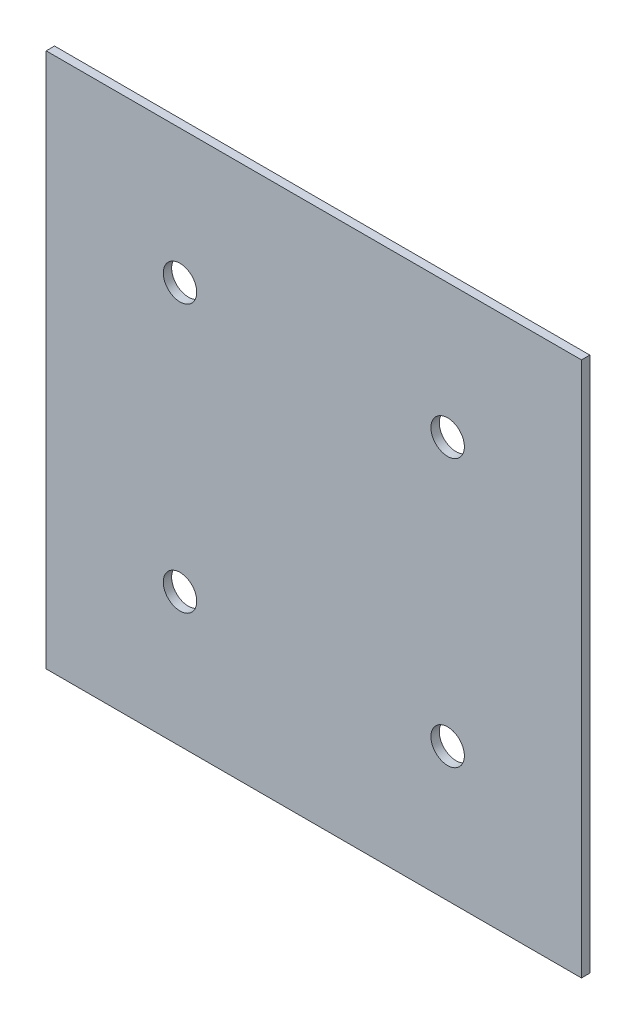
SolidWorks part; units mm, degrees
ref_plane "前视基准面" through (0, 0, 0) normal (0, 0, 1) x (1, 0, 0)
ref_plane "上视基准面" through (0, 0, 0) normal (0, 1, 0) x (1, 0, 0)
ref_plane "右视基准面" through (0, 0, 0) normal (1, 0, 0) x (0, 0, -1)
sketch "草图1" plane through (0, 0, 0) normal (0, 0, 1) x (1, 0, 0)
  line L1 (0, 0) -> (160, 0)
  line L2 (0, 0) -> (0, 160)
  line L3 (0, 160) -> (160, 160)
  line L4 (160, 0) -> (160, 160)
  dimension "D1" = 160
  dimension "D2" = 160
extrude "凸台-拉伸1" add sketch "草图1" along normal blind 2.5
sketch "草图2" plane through (0, 0, 2.5) normal (0, 0, 1) x (1, 0, 0)
  line L0 (0, 160) -> (0, 0) construction
  line L3 (160, 160) -> (0, 160) construction
  circle A0 centre (40, 120) radius 5
  dimension "D3" = 10
  dimension "D1" = 40
  dimension "D2" = 40
extrude "切除-拉伸1" cut sketch "草图2" against normal through all
pattern_linear "阵列(线性)1" count 2 spacing 80 along (1, 0, 0) count 2 spacing 80 along (0, -1, 0) of "切除-拉伸1"
